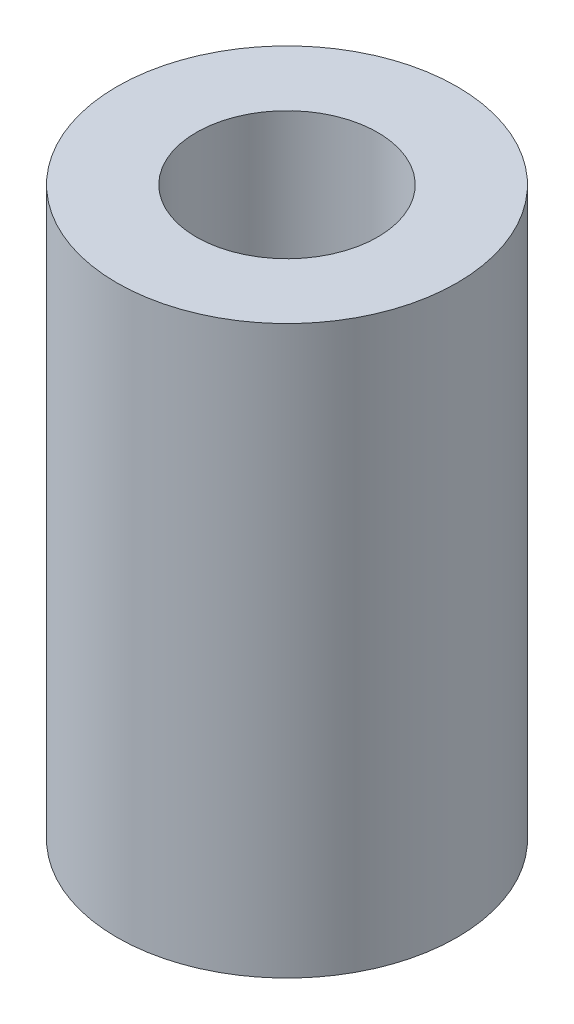
SolidWorks part; units mm, degrees
ref_plane "前基準面" through (0, 0, 0) normal (0, 0, 1) x (1, 0, 0)
ref_plane "上基準面" through (0, 0, 0) normal (0, 1, 0) x (1, 0, 0)
ref_plane "右基準面" through (0, 0, 0) normal (1, 0, 0) x (0, 0, -1)
sketch "草圖1" plane through (0, 0, 0) normal (0, 1, 0) x (1, 0, 0)
  circle A0 centre (0, 0) radius 1.6
  circle A1 centre (0, 0) radius 3
  dimension "D1" = 6
  dimension "D2" = 3.2
extrude "填料-伸長1" add sketch "草圖1" along normal blind 10
